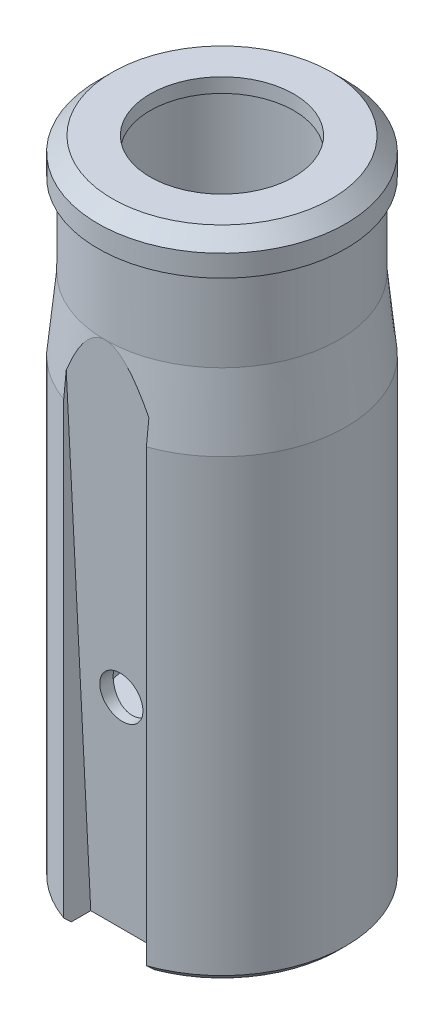
SolidWorks part; units mm, degrees
material "Chrome Stainless Steel"
ref_plane "Front Plane" through (0, 0, 0) normal (0, 0, 1) x (1, 0, 0)
ref_plane "Top Plane" through (0, 0, 0) normal (0, 1, 0) x (1, 0, 0)
ref_plane "Right Plane" through (0, 0, 0) normal (1, 0, 0) x (0, 0, -1)
sketch "MainBodyS" plane through (0, 0, 0) normal (0, 0, 1) x (1, 0, 0)
  line L1 (3.45, 0.2) -> (3.45, 12.7)
  line L2 (3.45, 12.7) -> (3.25, 14.7)
  line L3 (3.25, 14.7) -> (3.25, 17)
  line L4 (3.25, 17) -> (3.45, 17)
  line L5 (3.45, 17) -> (3.45, 17.6)
  line L6 (3.45, 17.6) -> (3.05, 18)
  line L7 (3.05, 18) -> (2, 18)
  line L8 (2, 18) -> (2, 17.6)
  line L9 (2, 17.6) -> (2.5, 17.6)
  line L10 (2.5, 17.6) -> (2.5, 4)
  line L11 (1.1, 0) -> (1.1, 4)
  line L12 (1.1, 4) -> (2.5, 4)
  line L13 (0, 0) -> (0, 18) construction
  line L14 (1.1, 0) -> (3.25, 0)
  line L15 (3.25, 0) -> (3.45, 0.2)
  dimension "BottomChamferAngle" = 45
  dimension "TopChamferAngle" = 45
  dimension "ChamferHeight" = 0.2
  dimension "TopChamferHeight" = 0.4
  dimension "Height" = 18
  dimension "TopHeight" = 1
  dimension "HeightMidDia" = 2.3
  dimension "MidDia" = 6.5
  dimension "Dia" = 6.9
  dimension "TopCoverThickness" = 0.4
  dimension "HeightBottomDia" = 4
  dimension "TopHoleDiaControl" = 1.25
  dimension "TopDiaRef" = 4
  dimension "BottomInnerDiaControl" = 2.35
  dimension "RefBottomDia" = 2.2
  dimension "HeightMidChamfer" = 2
  dimension "RefHeightTop" = 5.3
  dimension "RefHeightTopHalf" = 3.3
  dimension "MidInnerDiaControl" = 0.5
  dimension "D20" = 0.75
revolve "MAIN BODY" add sketch "MainBodyS" angle 360 about L13
ref_plane "SLOT END PLANE" through (0, 14.7, 0) normal (0, -1, 0) x (-1, 0, 0)
sketch "LoftedSlotStartS" plane through (0, 0, 0) normal (0, -1, 0) x (-1, 0, 0)
  line L0 (0, 0) -> (0, 2.975) construction
  line L1 (-1.15, 3.45) -> (1.15, 3.45)
  line L2 (-1.15, 3.45) -> (-1.15, 2.5)
  line L3 (-1.15, 2.5) -> (1.15, 2.5)
  line L4 (1.15, 3.45) -> (1.15, 2.5)
  line L5 (-1.15, 3.45) -> (1.15, 2.5) construction
  line L6 (-1.15, 2.5) -> (1.15, 3.45) construction
  circle A0 centre (0, 0) radius 3.45 construction
  point P0 (0, 2.975)
  dimension "Width" = 2.3
  dimension "Height" = 0.95
  dimension "RefHeight" = 2.5
sketch "LoftedSlotEndS" plane through (0, 14.7, 0) normal (0, -1, 0) x (-1, 0, 0)
  line L0 (0, 3.5) -> (0, 0) construction
  line L1 (-1.15, 3.75) -> (1.15, 3.75)
  line L2 (-1.15, 3.75) -> (-1.15, 3.25)
  line L3 (-1.15, 3.25) -> (1.15, 3.25)
  line L4 (1.15, 3.75) -> (1.15, 3.25)
  line L5 (-1.15, 3.75) -> (1.15, 3.25) construction
  line L6 (-1.15, 3.25) -> (1.15, 3.75) construction
  line L7 (-1.15, 3.45) -> (-1.15, 2.5) construction
  circle A0 centre (0, 0) radius 3.25 construction
  point P0 (0, 3.5)
  point P5 (0, 0)
  point P7 (0, 0)
  dimension "Height" = 0.5
loft "LOFTED SLOT" cut profiles "LoftedSlotEndS", "LoftedSlotStartS"
mirror "LS HM" about plane through (0, 0, 0) normal (0, 0, 1) of "LOFTED SLOT"
sketch "LocatingHoleS" plane through (0, -0.1272, 2.4935) normal (0, -0.051, 0.9987) x (1, 0, 0)
  line L0 (0, 0) -> (0, 6) construction
  circle A0 centre (0, 6) radius 0.6
  dimension "Dia" = 1.2
  dimension "Height" = 6
extrude "LOCATING HOLE" cut sketch "LocatingHoleS" against normal up to next
